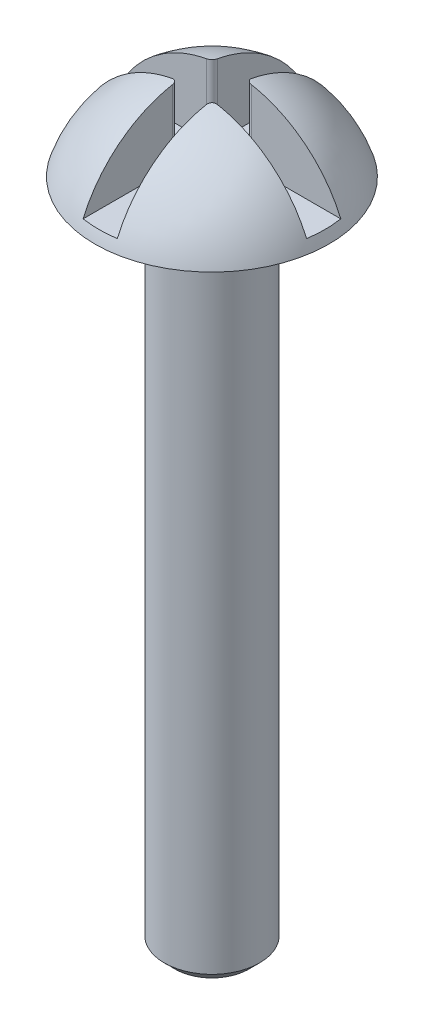
SolidWorks part; units mm, degrees
ref_plane "Front Plane" through (0, 0, 0) normal (0, 0, 1) x (1, 0, 0)
ref_plane "Top Plane" through (0, 0, 0) normal (0, 1, 0) x (1, 0, 0)
ref_plane "Right Plane" through (0, 0, 0) normal (1, 0, 0) x (0, 0, -1)
sketch "Sketch2" plane through (0, 0, 0) normal (1, 0, 0) x (0, 0, -1)
  line L0 (0, 0) -> (2.7813, 0)
  line L1 (0, 0) -> (0, 2.032)
  line L2 (0, 0.4152) -> (0, -1.08) construction
  arc A0 (2.7813, 0) -> (0, 2.032) centre (0, -0.8875) ccw
  dimension "D1" = 2.7813
  dimension "D2" = 2.032
revolve "Head" add sketch "Sketch2" angle 360 about L2
sketch "Sketch3" plane through (0, 0, 0) normal (0, -1, 0) x (1, 0, 0)
  circle A0 centre (0, 0) radius 1.1303
  dimension "D1" = 2.2606
extrude "Shaft" add sketch "Sketch3" along normal blind 15.875
chamfer "Tip" distance 0.254 angle 45 1 edges at (0, -15.875, -1.1303)
sketch "Sketch4" plane through (0, 0, 0) normal (0, 1, 0) x (1, 0, 0)
  line L0 (-0.4064, 0.4064) -> (-0.4064, 2.7813)
  line L1 (-0.4064, -2.7813) -> (0.4064, -2.7813)
  line L2 (-0.4064, -2.7813) -> (-0.4064, -0.4064)
  line L3 (-0.4064, 2.7813) -> (0.4064, 2.7813)
  line L4 (0.4064, -2.7813) -> (0.4064, -0.4064)
  line L5 (-0.4064, -2.7813) -> (0.4064, 2.7813) construction
  line L6 (-0.4064, 2.7813) -> (0.4064, -2.7813) construction
  line L7 (2.7813, -0.4064) -> (0.4064, -0.4064)
  line L8 (2.7813, -0.4064) -> (2.7813, 0.4064)
  line L9 (2.7813, 0.4064) -> (0.4064, 0.4064)
  line L10 (-2.7813, -0.4064) -> (-2.7813, 0.4064)
  line L11 (2.7813, -0.4064) -> (-2.7813, 0.4064) construction
  line L12 (2.7813, 0.4064) -> (-2.7813, -0.4064) construction
  line L13 (-0.4064, -0.4064) -> (-2.7813, -0.4064)
  line L15 (0.4064, 0.4064) -> (0.4064, 2.7813)
  line L17 (-0.4064, 0.4064) -> (-2.7813, 0.4064)
  circle A0 centre (0, 0) radius 2.7813 construction
  point P0 (0, 0)
  point P8 (0, 0)
  dimension "D1" = 0.8128
extrude "Phillips" cut sketch "Sketch4" along normal through all from offset 0.254
fillet "PhillipsFillet" radius 0.127 4 edges at (0.4064, 1.1144, 0.4064) (0.4064, 1.1144, -0.4064) (-0.4064, 1.1144, 0.4064) (-0.4064, 1.1144, -0.4064)
